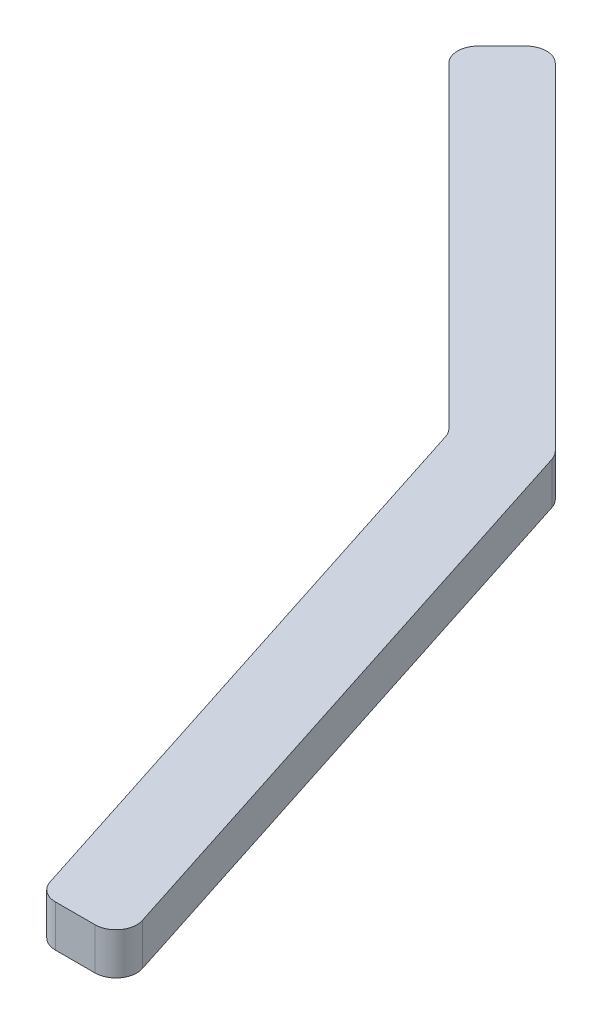
SolidWorks part; units mm, degrees
ref_plane "Front Plane" through (0, 0, 0) normal (0, 0, 1) x (1, 0, 0)
ref_plane "Top Plane" through (0, 0, 0) normal (0, 1, 0) x (1, 0, 0)
ref_plane "Right Plane" through (0, 0, 0) normal (1, 0, 0) x (0, 0, -1)
sketch "Sketch1" plane through (0, 0, 0) normal (0, 1, 0) x (1, 0, 0)
  line L0 (-2.6717, 8.2965) -> (-60.7832, 188.7478)
  line L1 (-65.7566, 196.8875) -> (-165.5601, 296.691)
  line L2 (-174.5404, 296.691) -> (-181.7246, 289.5068)
  line L3 (-181.7246, 280.5265) -> (-85.4801, 184.2821)
  line L4 (-83.9259, 181.7384) -> (-26.8181, 4.4035)
  line L5 (-20.7738, 0) -> (-8.7161, 0)
  line L6 (-65.7566, 196.8875) -> (-63.3714, 194.5023)
  line L7 (-61.8172, 191.9586) -> (-60.7832, 188.7478)
  arc A0 (-8.7161, 0) -> (-2.6717, 8.2965) centre (-8.7161, 6.35) ccw
  arc A1 (-20.7738, 0) -> (-26.8181, 4.4035) centre (-20.7738, 6.35) cw
  arc A2 (-61.8172, 191.9586) -> (-63.3714, 194.5023) centre (-67.8615, 190.0121) ccw
  arc A3 (-83.9259, 181.7384) -> (-85.4801, 184.2821) centre (-89.9703, 179.792) ccw
  arc A4 (-181.7246, 289.5068) -> (-181.7246, 280.5265) centre (-177.2345, 285.0167) ccw
  arc A5 (-165.5601, 296.691) -> (-174.5404, 296.691) centre (-170.0502, 292.2009) ccw
  point P9 (0, 0)
  point P12 (-25.4, 0)
  point P15 (-62.2872, 193.4181)
  point P22 (-170.0502, 301.1811)
  dimension "D4" = 6.35
  dimension "D5" = 10.16
  dimension "D1" = 203.2
  dimension "D2" = 152.4
  dimension "D3" = 25.4
extrude "Boss-Extrude1" add sketch "Sketch1" along normal blind 12.7
